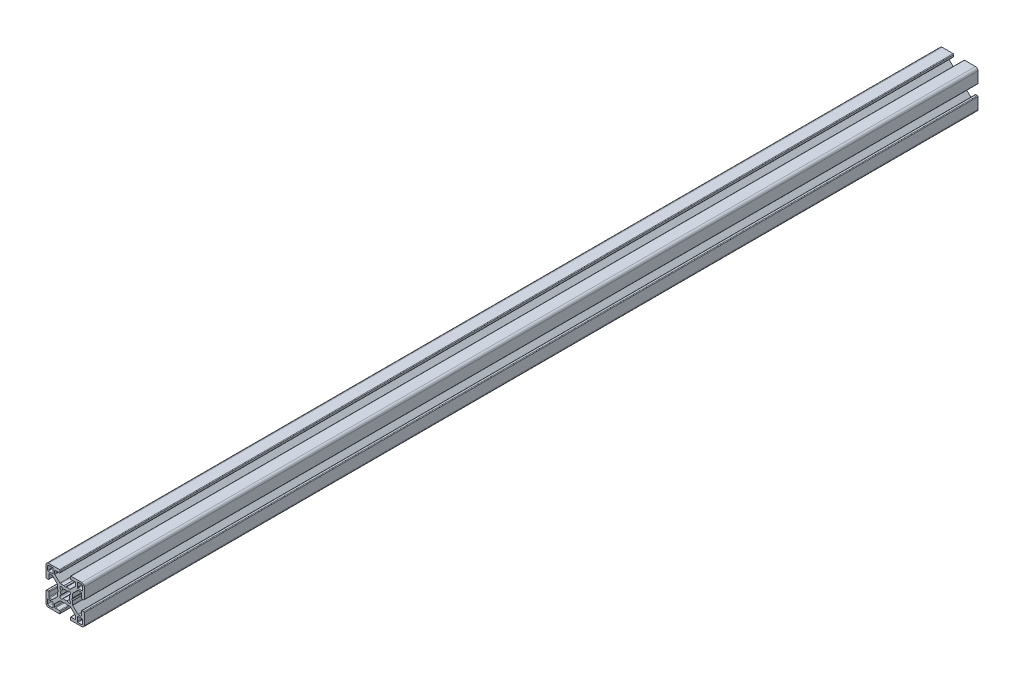
SolidWorks part; units mm, degrees
material "6105-T5 Aluminum"
ref_plane "Front Plane" through (0, 0, 0) normal (0, 0, 1) x (1, 0, 0)
ref_plane "Top Plane" through (0, 0, 0) normal (0, 1, 0) x (1, 0, 0)
ref_plane "Right Plane" through (0, 0, 0) normal (1, 0, 0) x (0, 0, -1)
sketch "Sketch1" plane through (0, 0, 0) normal (0, 0, 1) x (1, 0, 0)
  line L0 (9.5, -13.3189) -> (9.5, -9.88)
  line L1 (9.88, -9.5) -> (13.3189, -9.5)
  line L2 (13.6999, -9.881) -> (13.6999, -12.6999)
  line L3 (12.6999, -13.6999) -> (9.881, -13.6999)
  line L4 (-13.3189, -9.5) -> (-9.88, -9.5)
  line L5 (-9.5, -9.88) -> (-9.5, -13.3189)
  line L6 (-9.881, -13.6999) -> (-12.6999, -13.6999)
  line L7 (-13.6999, -12.6999) -> (-13.6999, -9.881)
  line L8 (-1.4942, -3.1981) -> (-2.4733, -3.9799)
  line L9 (-3.9799, -2.4733) -> (-3.1981, -1.4942)
  line L10 (-3.1981, 1.4942) -> (-3.9799, 2.4733)
  line L11 (-2.4733, 3.9799) -> (-1.4942, 3.1981)
  line L12 (1.4942, 3.1981) -> (2.4733, 3.9799)
  line L13 (3.9799, 2.4733) -> (3.1981, 1.4942)
  line L14 (3.1981, -1.4942) -> (3.9799, -2.4733)
  line L15 (2.4733, -3.9799) -> (1.4942, -3.1981)
  line L16 (-9.5, 13.3189) -> (-9.5, 9.88)
  line L17 (-9.88, 9.5) -> (-13.3189, 9.5)
  line L18 (-13.6999, 9.881) -> (-13.6999, 12.6999)
  line L19 (-12.6999, 13.6999) -> (-9.881, 13.6999)
  line L20 (9.881, 13.6999) -> (12.6999, 13.6999)
  line L21 (13.6999, 12.6999) -> (13.6999, 9.881)
  line L22 (13.3189, 9.5) -> (9.88, 9.5)
  line L23 (9.5, 9.88) -> (9.5, 13.3189)
  line L24 (12.7425, -4.5) -> (12.7425, -7.7325)
  line L25 (12.2428, -8.25) -> (10.2602, -8.25)
  line L26 (9.9066, -8.1035) -> (5.9811, -4.178)
  line L27 (5.8347, -3.8245) -> (5.8347, -1.0125)
  line L28 (5.8347, -1.0125) -> (5.3247, -0.0625)
  line L29 (5.3247, -0.0625) -> (5.8347, 0.8875)
  line L30 (5.8347, 0.8875) -> (5.8347, 3.8245)
  line L31 (5.9811, 4.178) -> (9.9066, 8.1035)
  line L32 (10.2602, 8.25) -> (12.2428, 8.25)
  line L33 (12.7425, 7.7325) -> (12.7425, 4.5)
  line L34 (13.2425, 4) -> (14.4999, 4)
  line L35 (14.9999, 4.5) -> (14.9999, 12.9999)
  line L36 (12.9999, 14.9999) -> (4.5, 14.9999)
  line L37 (4, 14.4999) -> (4, 13.2425)
  line L38 (4.5, 12.7425) -> (7.7325, 12.7425)
  line L39 (8.25, 12.2428) -> (8.25, 10.2602)
  line L40 (8.1035, 9.9066) -> (4.178, 5.9811)
  line L41 (3.8245, 5.8347) -> (0.95, 5.8347)
  line L42 (0.95, 5.8347) -> (0, 5.3247)
  line L43 (0, 5.3247) -> (-0.95, 5.8347)
  line L44 (-0.95, 5.8347) -> (-3.8245, 5.8347)
  line L45 (-4.178, 5.9811) -> (-8.1035, 9.9066)
  line L46 (-8.25, 10.2602) -> (-8.25, 12.2428)
  line L47 (-7.7325, 12.7425) -> (-4.5, 12.7425)
  line L48 (-4, 13.2425) -> (-4, 14.4999)
  line L49 (-4.5, 14.9999) -> (-12.9999, 14.9999)
  line L50 (-14.9999, 12.9999) -> (-14.9999, 4.5)
  line L51 (-14.4999, 4) -> (-13.2425, 4)
  line L52 (-12.7425, 4.5) -> (-12.7425, 7.7325)
  line L53 (-12.2428, 8.25) -> (-10.2602, 8.25)
  line L54 (-9.9066, 8.1035) -> (-5.9811, 4.178)
  line L55 (-5.8347, 3.8245) -> (-5.8347, 0.8875)
  line L56 (-5.8347, 0.8875) -> (-5.3247, -0.0625)
  line L57 (-5.3247, -0.0625) -> (-5.8347, -1.0125)
  line L58 (-5.8347, -1.0125) -> (-5.8347, -3.8245)
  line L59 (-5.9811, -4.178) -> (-9.9066, -8.1035)
  line L60 (-10.2602, -8.25) -> (-12.2428, -8.25)
  line L61 (-12.7425, -7.7325) -> (-12.7425, -4.5)
  line L62 (-13.2425, -4) -> (-14.4999, -4)
  line L63 (-14.9999, -4.5) -> (-14.9999, -12.9999)
  line L64 (-12.9999, -14.9999) -> (-4.5, -14.9999)
  line L65 (-4, -14.4999) -> (-4, -13.2425)
  line L66 (-4.5, -12.7425) -> (-7.7325, -12.7425)
  line L67 (-8.25, -12.2428) -> (-8.25, -10.2602)
  line L68 (-8.1035, -9.9066) -> (-4.178, -5.9811)
  line L69 (-3.8245, -5.8347) -> (-0.95, -5.8347)
  line L70 (-0.95, -5.8347) -> (0, -5.3247)
  line L71 (0, -5.3247) -> (0.95, -5.8347)
  line L72 (0.95, -5.8347) -> (3.8245, -5.8347)
  line L73 (4.178, -5.9811) -> (8.1035, -9.9066)
  line L74 (8.25, -10.2602) -> (8.25, -12.2428)
  line L75 (7.7325, -12.7425) -> (4.5, -12.7425)
  line L76 (4, -13.2425) -> (4, -14.4999)
  line L77 (4.5, -14.9999) -> (12.9999, -14.9999)
  line L78 (14.9999, -12.9999) -> (14.9999, -4.5)
  line L79 (14.4999, -4) -> (13.2425, -4)
  arc A0 (9.5, -13.3189) -> (9.881, -13.6999) centre (9.881, -13.3189) ccw
  arc A1 (9.88, -9.5) -> (9.5, -9.88) centre (9.88, -9.88) ccw
  arc A2 (13.6999, -9.881) -> (13.3189, -9.5) centre (13.3189, -9.881) ccw
  arc A3 (12.6999, -13.6999) -> (13.6999, -12.6999) centre (12.6999, -12.6999) ccw
  arc A4 (-13.3189, -9.5) -> (-13.6999, -9.881) centre (-13.3189, -9.881) ccw
  arc A5 (-9.5, -9.88) -> (-9.88, -9.5) centre (-9.88, -9.88) ccw
  arc A6 (-9.881, -13.6999) -> (-9.5, -13.3189) centre (-9.881, -13.3189) ccw
  arc A7 (-13.6999, -12.6999) -> (-12.6999, -13.6999) centre (-12.6999, -12.6999) ccw
  arc A8 (-1.4942, -3.1981) -> (1.4942, -3.1981) centre (0, 0) ccw
  arc A9 (-3.9799, -2.4733) -> (-2.4733, -3.9799) centre (-3.1422, -3.1422) ccw
  arc A10 (-3.1981, 1.4942) -> (-3.1981, -1.4942) centre (0, 0) ccw
  arc A11 (-2.4733, 3.9799) -> (-3.9799, 2.4733) centre (-3.1422, 3.1422) ccw
  arc A12 (1.4942, 3.1981) -> (-1.4942, 3.1981) centre (0, 0) ccw
  arc A13 (3.9799, 2.4733) -> (2.4733, 3.9799) centre (3.1422, 3.1422) ccw
  arc A14 (3.1981, -1.4942) -> (3.1981, 1.4942) centre (0, 0) ccw
  arc A15 (2.4733, -3.9799) -> (3.9799, -2.4733) centre (3.1422, -3.1422) ccw
  arc A16 (-9.5, 13.3189) -> (-9.881, 13.6999) centre (-9.881, 13.3189) ccw
  arc A17 (-9.88, 9.5) -> (-9.5, 9.88) centre (-9.88, 9.88) ccw
  arc A18 (-13.6999, 9.881) -> (-13.3189, 9.5) centre (-13.3189, 9.881) ccw
  arc A19 (-12.6999, 13.6999) -> (-13.6999, 12.6999) centre (-12.6999, 12.6999) ccw
  arc A20 (9.881, 13.6999) -> (9.5, 13.3189) centre (9.881, 13.3189) ccw
  arc A21 (13.6999, 12.6999) -> (12.6999, 13.6999) centre (12.6999, 12.6999) ccw
  arc A22 (13.3189, 9.5) -> (13.6999, 9.881) centre (13.3189, 9.881) ccw
  arc A23 (9.5, 9.88) -> (9.88, 9.5) centre (9.88, 9.88) ccw
  arc A24 (13.2425, -4) -> (12.7425, -4.5) centre (13.2425, -4.5) ccw
  arc A25 (12.2428, -8.25) -> (12.7425, -7.7325) centre (12.2428, -7.75) ccw
  arc A26 (9.9066, -8.1035) -> (10.2602, -8.25) centre (10.2602, -7.75) ccw
  arc A27 (5.8347, -3.8245) -> (5.9811, -4.178) centre (6.3347, -3.8245) ccw
  arc A28 (5.9811, 4.178) -> (5.8347, 3.8245) centre (6.3347, 3.8245) ccw
  arc A29 (10.2602, 8.25) -> (9.9066, 8.1035) centre (10.2602, 7.75) ccw
  arc A30 (12.7425, 7.7325) -> (12.2428, 8.25) centre (12.2428, 7.75) ccw
  arc A31 (12.7425, 4.5) -> (13.2425, 4) centre (13.2425, 4.5) ccw
  arc A32 (14.4999, 4) -> (14.9999, 4.5) centre (14.4999, 4.5) ccw
  arc A33 (14.9999, 12.9999) -> (12.9999, 14.9999) centre (12.9999, 12.9999) ccw
  arc A34 (4.5, 14.9999) -> (4, 14.4999) centre (4.5, 14.4999) ccw
  arc A35 (4, 13.2425) -> (4.5, 12.7425) centre (4.5, 13.2425) ccw
  arc A36 (8.25, 12.2428) -> (7.7325, 12.7425) centre (7.75, 12.2428) ccw
  arc A37 (8.1035, 9.9066) -> (8.25, 10.2602) centre (7.75, 10.2602) ccw
  arc A38 (3.8245, 5.8347) -> (4.178, 5.9811) centre (3.8245, 6.3347) ccw
  arc A39 (-4.178, 5.9811) -> (-3.8245, 5.8347) centre (-3.8245, 6.3347) ccw
  arc A40 (-8.25, 10.2602) -> (-8.1035, 9.9066) centre (-7.75, 10.2602) ccw
  arc A41 (-7.7325, 12.7425) -> (-8.25, 12.2428) centre (-7.75, 12.2428) ccw
  arc A42 (-4.5, 12.7425) -> (-4, 13.2425) centre (-4.5, 13.2425) ccw
  arc A43 (-4, 14.4999) -> (-4.5, 14.9999) centre (-4.5, 14.4999) ccw
  arc A44 (-12.9999, 14.9999) -> (-14.9999, 12.9999) centre (-12.9999, 12.9999) ccw
  arc A45 (-14.9999, 4.5) -> (-14.4999, 4) centre (-14.4999, 4.5) ccw
  arc A46 (-13.2425, 4) -> (-12.7425, 4.5) centre (-13.2425, 4.5) ccw
  arc A47 (-12.2428, 8.25) -> (-12.7425, 7.7325) centre (-12.2428, 7.75) ccw
  arc A48 (-9.9066, 8.1035) -> (-10.2602, 8.25) centre (-10.2602, 7.75) ccw
  arc A49 (-5.8347, 3.8245) -> (-5.9811, 4.178) centre (-6.3347, 3.8245) ccw
  arc A50 (-5.9811, -4.178) -> (-5.8347, -3.8245) centre (-6.3347, -3.8245) ccw
  arc A51 (-10.2602, -8.25) -> (-9.9066, -8.1035) centre (-10.2602, -7.75) ccw
  arc A52 (-12.7425, -7.7325) -> (-12.2428, -8.25) centre (-12.2428, -7.75) ccw
  arc A53 (-12.7425, -4.5) -> (-13.2425, -4) centre (-13.2425, -4.5) ccw
  arc A54 (-14.4999, -4) -> (-14.9999, -4.5) centre (-14.4999, -4.5) ccw
  arc A55 (-14.9999, -12.9999) -> (-12.9999, -14.9999) centre (-12.9999, -12.9999) ccw
  arc A56 (-4.5, -14.9999) -> (-4, -14.4999) centre (-4.5, -14.4999) ccw
  arc A57 (-4, -13.2425) -> (-4.5, -12.7425) centre (-4.5, -13.2425) ccw
  arc A58 (-8.25, -12.2428) -> (-7.7325, -12.7425) centre (-7.75, -12.2428) ccw
  arc A59 (-8.1035, -9.9066) -> (-8.25, -10.2602) centre (-7.75, -10.2602) ccw
  arc A60 (-3.8245, -5.8347) -> (-4.178, -5.9811) centre (-3.8245, -6.3347) ccw
  arc A61 (4.178, -5.9811) -> (3.8245, -5.8347) centre (3.8245, -6.3347) ccw
  arc A62 (8.25, -10.2602) -> (8.1035, -9.9066) centre (7.75, -10.2602) ccw
  arc A63 (7.7325, -12.7425) -> (8.25, -12.2428) centre (7.75, -12.2428) ccw
  arc A64 (4.5, -12.7425) -> (4, -13.2425) centre (4.5, -13.2425) ccw
  arc A65 (4, -14.4999) -> (4.5, -14.9999) centre (4.5, -14.4999) ccw
  arc A66 (12.9999, -14.9999) -> (14.9999, -12.9999) centre (12.9999, -12.9999) ccw
  arc A67 (14.9999, -4.5) -> (14.4999, -4) centre (14.4999, -4.5) ccw
extrude "Extrude1" add sketch "Sketch1" against normal blind 700
